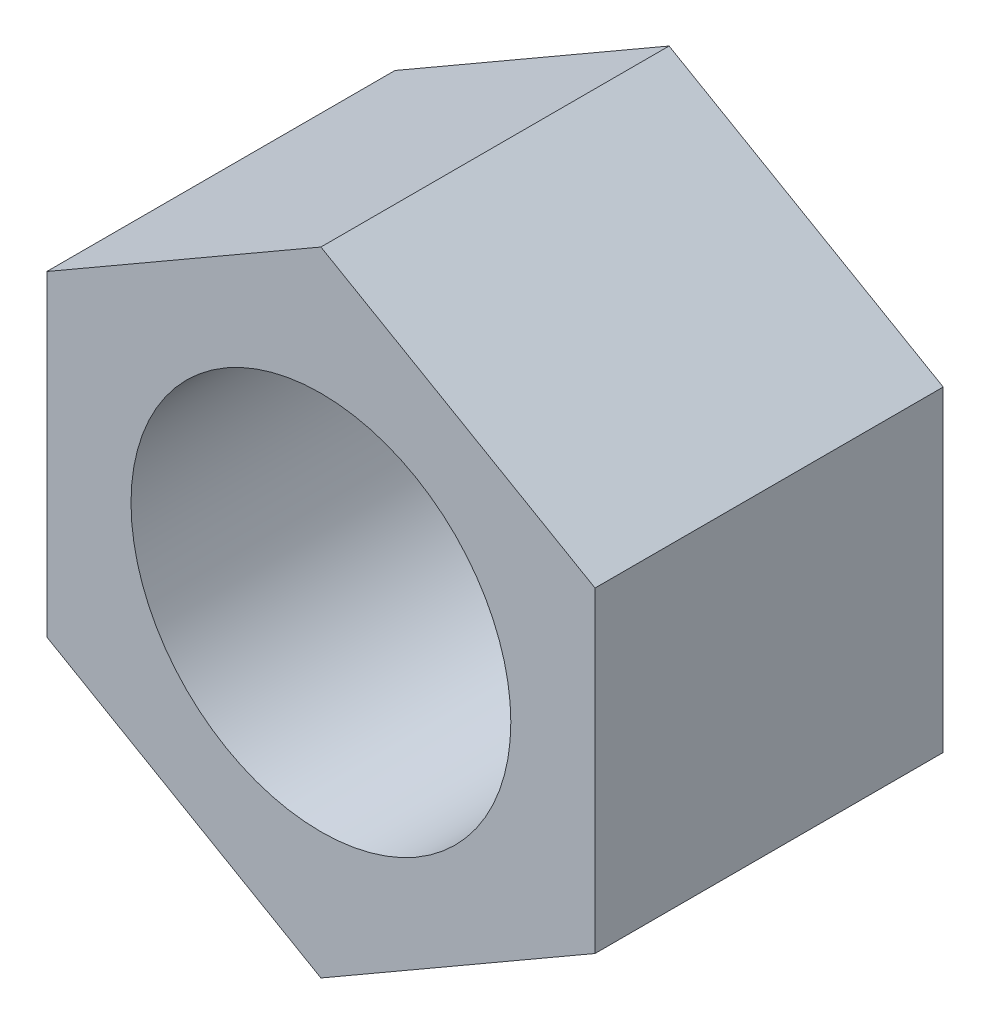
SolidWorks part; units mm, degrees
ref_plane "Front Plane" through (0, 0, 0) normal (1, 0, 0) x (0, 1, 0)
ref_plane "Top Plane" through (0, 0, 0) normal (0, 0, 1) x (0, 1, 0)
ref_plane "Right Plane" through (0, 0, 0) normal (0, 1, 0) x (-1, 0, 0)
sketch "Sketch1" plane through (0, 0, 0) normal (0, 0, 1) x (0, 1, 0)
  line L1 (5, 0) -> (2.5, 4.3301)
  line L2 (2.5, 4.3301) -> (-2.5, 4.3301)
  line L3 (-2.5, 4.3301) -> (-5, 0)
  line L4 (-5, 0) -> (-2.5, -4.3301)
  line L5 (-2.5, -4.3301) -> (2.5, -4.3301)
  line L6 (2.5, -4.3301) -> (5, 0)
  circle A0 centre (0, 0) radius 4.3301 construction
  point P1 (0, 0)
  dimension "D1" = 10
extrude "Boss-Extrude1" add sketch "Sketch1" along normal blind 5.5
sketch "Sketch2" plane through (0, 0, 5.5) normal (0, 0, 1) x (1, 0, 0)
  circle A0 centre (0, 0) radius 3
  dimension "D1" = 6
extrude "Cut-Extrude1" cut sketch "Sketch2" against normal up to next
